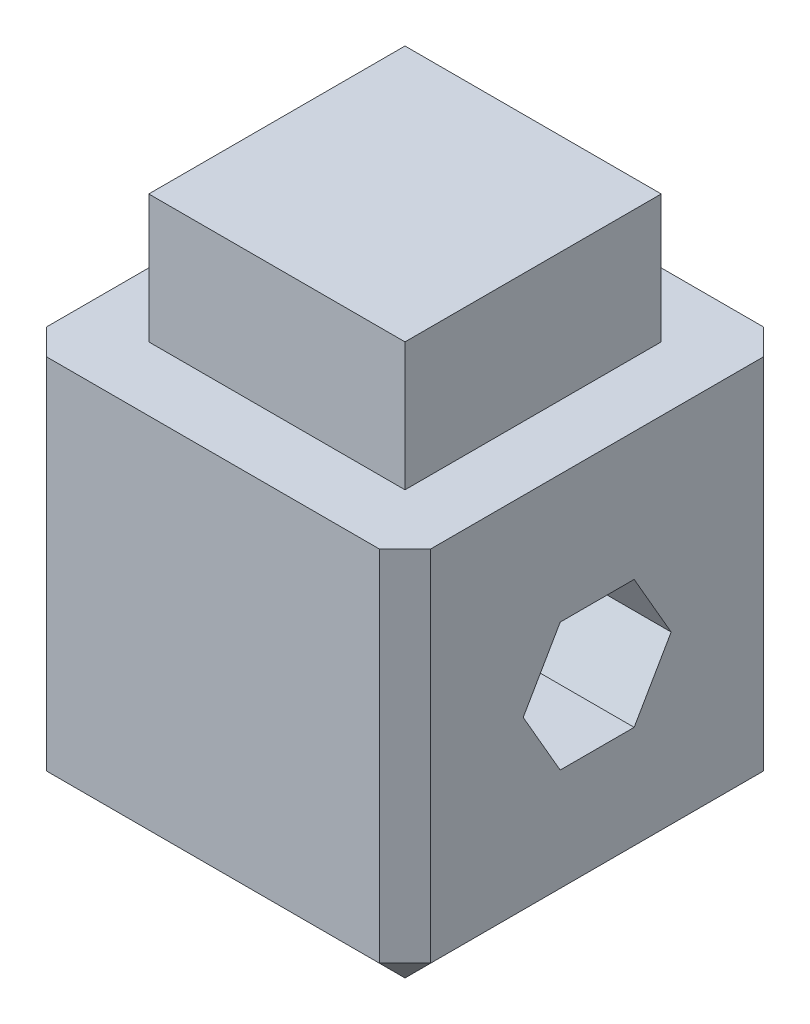
SolidWorks part; units mm, degrees
ref_plane "Front" through (0, 0, 0) normal (0, 0, 1) x (1, 0, 0)
ref_plane "Top" through (0, 0, 0) normal (0, 1, 0) x (1, 0, 0)
ref_plane "Right" through (0, 0, 0) normal (1, 0, 0) x (0, 0, -1)
sketch "Sketch1" plane through (0, 0, 0) normal (0, 1, 0) x (1, 0, 0)
  line L1 (-19.05, -19.05) -> (19.05, -19.05)
  line L2 (-19.05, -19.05) -> (-19.05, 19.05)
  line L3 (-19.05, 19.05) -> (19.05, 19.05)
  line L4 (19.05, -19.05) -> (19.05, 19.05)
  line L5 (-19.05, -19.05) -> (19.05, 19.05) construction
  line L6 (-19.05, 19.05) -> (19.05, -19.05) construction
  point P0 (0, 0)
  dimension "D1" = 38.1
extrude "Boss-Extrude1" add sketch "Sketch1" along normal blind 50.8
sketch "Sketch2" plane through (0, 50.8, 0) normal (0, 1, 0) x (1, 0, 0)
  line L1 (-19.05, -19.05) -> (19.05, -19.05)
  line L2 (-19.05, -19.05) -> (-19.05, 19.05)
  line L3 (-19.05, 19.05) -> (19.05, 19.05)
  line L4 (19.05, -19.05) -> (19.05, 19.05)
  line L5 (-19.05, -19.05) -> (19.05, 19.05) construction
  line L6 (-19.05, 19.05) -> (19.05, -19.05) construction
  line L7 (-12.7, -12.7) -> (12.7, -12.7)
  line L8 (-12.7, -12.7) -> (-12.7, 12.7)
  line L9 (-12.7, 12.7) -> (12.7, 12.7)
  line L10 (12.7, -12.7) -> (12.7, 12.7)
  line L11 (-12.7, -12.7) -> (12.7, 12.7) construction
  line L12 (-12.7, 12.7) -> (12.7, -12.7) construction
  point P0 (0, 0)
  point P5 (0, 0)
  dimension "D1" = 12.7
extrude "Cut-Extrude1" cut sketch "Sketch2" against normal blind 12.7
sketch "Sketch3" plane through (19.05, 0, 0) normal (1, 0, 0) x (0, 0, -1)
  line L0 (-19.05, 38.1) -> (19.05, 0) construction
  line L3 (-19.05, 38.1) -> (-19.05, 0) construction
  line L4 (-7.3323, 19.05) -> (-3.6662, 12.7)
  line L5 (-3.6662, 12.7) -> (3.6662, 12.7)
  line L6 (3.6662, 12.7) -> (7.3323, 19.05)
  line L7 (7.3323, 19.05) -> (3.6662, 25.4)
  line L8 (3.6662, 25.4) -> (-3.6662, 25.4)
  line L9 (-3.6662, 25.4) -> (-7.3323, 19.05)
  circle A0 centre (0, 19.05) radius 6.35 construction
  point P4 (-7.3323, 19.05)
  point P18 (-19.05, 19.05)
  dimension "D1" = 12.7
extrude "Cut-Extrude2" cut sketch "Sketch3" against normal through all
chamfer "Chamfer1" distance 2.54 angle 45 8 edges at (-19.05, 19.05, -19.05) (-19.05, 19.05, 19.05) (-19.05, 0, 0) (0, 0, -19.05) (19.05, 19.05, -19.05) (19.05, 19.05, 19.05) (19.05, 0, 0) (0, 0, 19.05)
